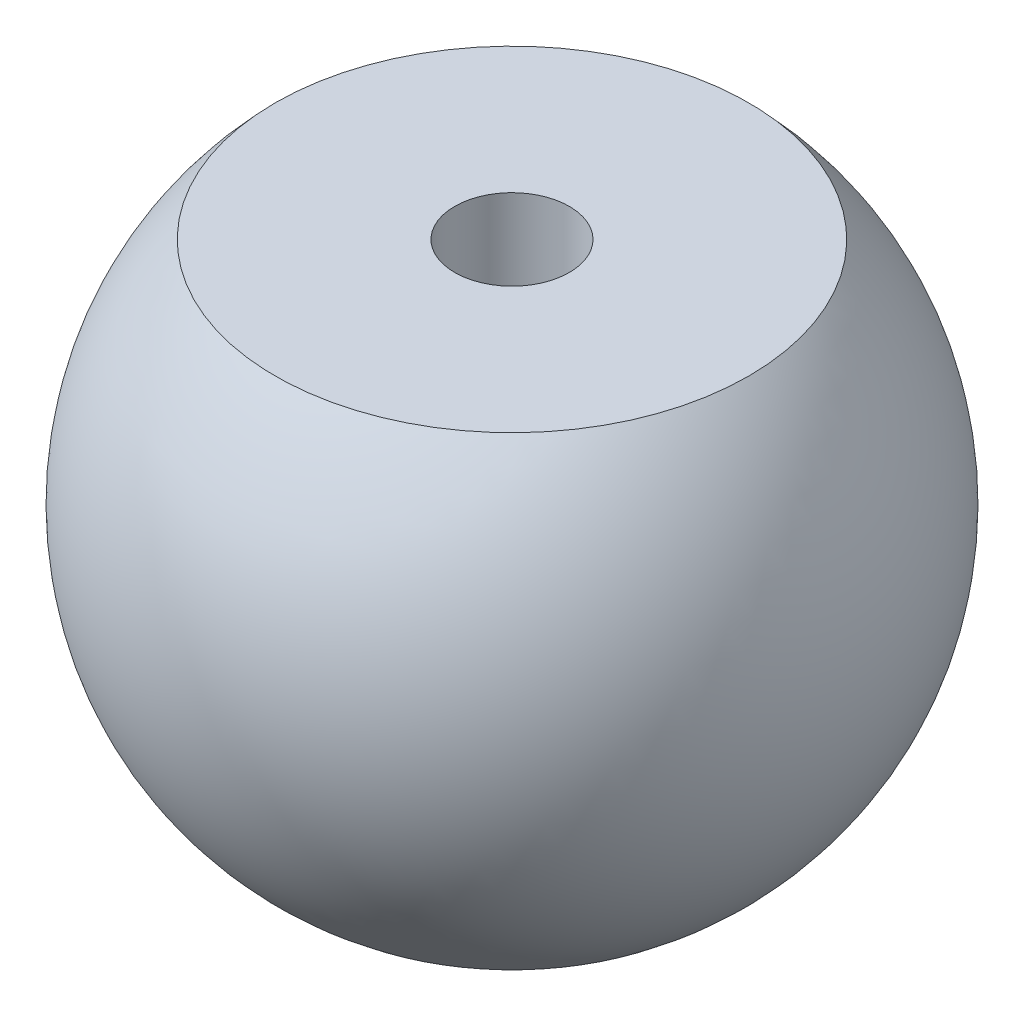
SolidWorks part; units mm, degrees
ref_plane "Front Plane" through (0, 0, 0) normal (0, 0, 1) x (1, 0, 0)
ref_plane "Top Plane" through (0, 0, 0) normal (0, 1, 0) x (1, 0, 0)
ref_plane "Right Plane" through (0, 0, 0) normal (1, 0, 0) x (0, 0, -1)
sketch "Sketch1" plane through (0, 0, 0) normal (0, 0, 1) x (1, 0, 0)
  line L0 (0, 18.2815) -> (0, -1.7185) construction
  line L1 (2, 8) -> (8.2614, 8)
  line L2 (2, -11) -> (3.3541, -11)
  line L3 (0, 0) -> (15, 0) construction
  line L4 (9.6047, 8) -> (12.6886, 8)
  line L5 (5.9372, -11) -> (10.198, -11)
  line L6 (2, 8) -> (2, 2.4155)
  line L7 (2, 2.4155) -> (2, -11)
  arc A0 (10.198, -11) -> (12.6886, 8) centre (0, 0) ccw
  arc A1 (5.9372, -11) -> (9.6047, 8) centre (0, 0) ccw
  arc A2 (3.3541, -11) -> (8.2614, 8) centre (0, 0) ccw
  dimension "D4" = 15
  dimension "D5" = 11.5
  dimension "D6" = 12.5
  dimension "D1" = 11
  dimension "D2" = 2
  dimension "D3" = 8
revolve "Revolve1" add sketch "Sketch1" angle 360 about L0
